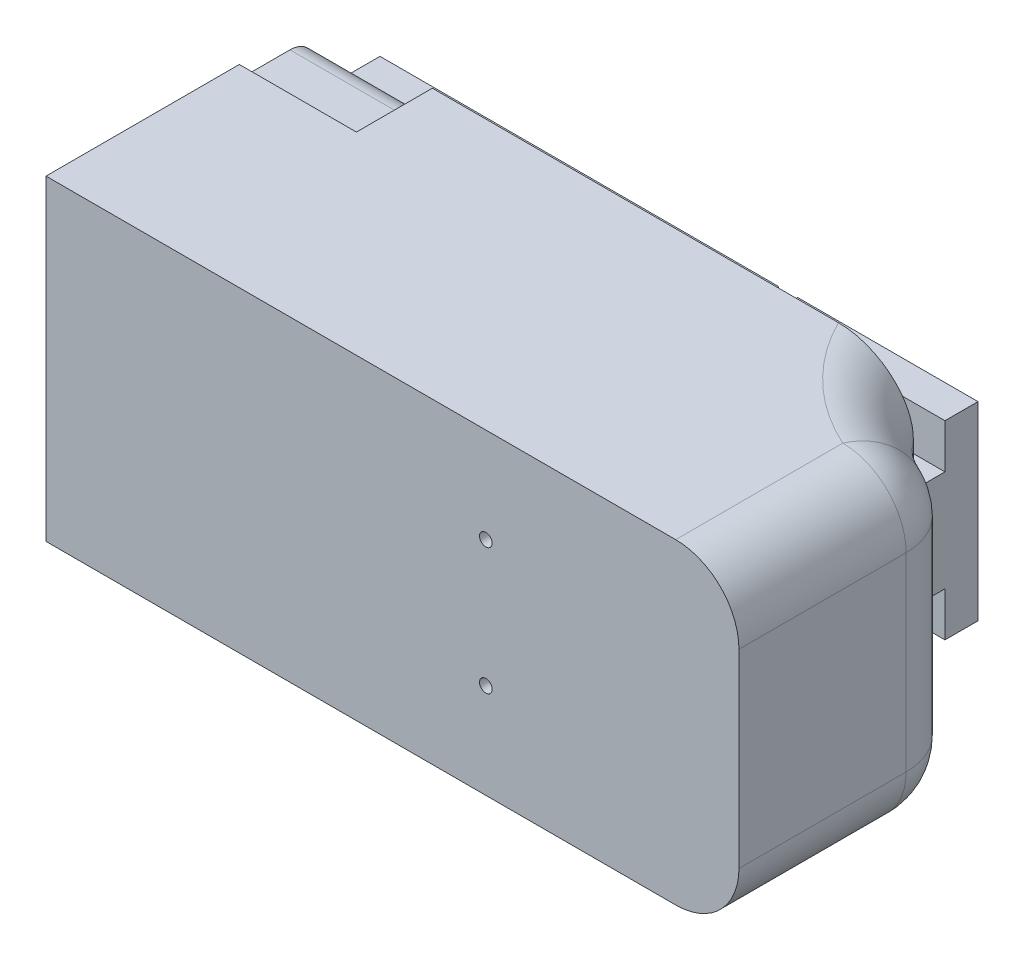
SolidWorks part; units mm, degrees
ref_plane "Front Plane" through (0, 0, 0) normal (0, 0, 1) x (1, 0, 0)
ref_plane "Top Plane" through (0, 0, 0) normal (0, 1, 0) x (1, 0, 0)
ref_plane "Right Plane" through (0, 0, 0) normal (1, 0, 0) x (0, 0, -1)
sketch "Sketch1" plane through (0, 0, 0) normal (0, 0, 1) x (1, 0, 0)
  line L0 (0, 0) -> (0, 50)
  line L1 (0, 50) -> (109.5, 50)
  line L2 (109.5, 50) -> (109.5, 0)
  line L3 (109.5, 0) -> (0, 0)
  dimension "D1" = 109.5
  dimension "D2" = 50
extrude "Boss-Extrude1" add sketch "Sketch1" along normal blind 52.55
sketch "Sketch2" plane through (0, 0, 0) normal (0, -1, 0) x (1, 0, 0)
  line L0 (0, 10) -> (109.5, 10)
  line L1 (0, 52.55) -> (0, 0) construction
  line L2 (109.5, 52.55) -> (109.5, 0) construction
  line L3 (0, 52.55) -> (109.5, 52.55) construction
  line L4 (0, 10) -> (0, 0)
  line L5 (0, 0) -> (109.5, 0)
  line L6 (109.5, 0) -> (109.5, 10)
  dimension "D1" = 42.55
extrude "Cut-Extrude1" cut sketch "Sketch2" against normal blind 10
sketch "Sketch3" plane through (0, 0, 0) normal (0, -1, 0) x (1, 0, 0)
  line L0 (0, 22) -> (18.5, 22)
  line L1 (0, 52.55) -> (0, 10) construction
  line L2 (18.5, 22) -> (18.5, 10)
  line L3 (109.5, 10) -> (0, 10) construction
  line L4 (0, 22) -> (0, 10)
  line L5 (0, 10) -> (18.5, 10)
  dimension "D1" = 18.5
  dimension "D2" = 12
extrude "Cut-Extrude2" cut sketch "Sketch3" against normal blind 2
fillet "Fillet1" radius 4 1 edges at (9.25, 2, 10)
sketch "Sketch4" plane through (0, 10, 0) normal (0, -1, 0) x (1, 0, 0)
  line L0 (18.5, 10) -> (18.5, 5)
  line L1 (109.5, 10) -> (0, 10) construction
  line L2 (18.5, 5) -> (109.5, 5)
  line L3 (109.5, 0) -> (109.5, 10) construction
  line L4 (109.5, 5) -> (109.5, 10)
  line L5 (109.5, 10) -> (18.5, 10)
  line L6 (0, 10) -> (0, 0) construction
  dimension "D1" = 18.5
  dimension "D2" = 5
extrude "Cut-Extrude3" cut sketch "Sketch4" against normal blind 7
sketch "Sketch5" plane through (0, 10, 0) normal (0, -1, 0) x (1, 0, 0)
  line L0 (94.5, 0) -> (94.5, 10)
  line L1 (0, 0) -> (109.5, 0) construction
  line L2 (109.5, 52.55) -> (109.5, 10) construction
  line L3 (94.5, 10) -> (117.8937, 10)
  line L4 (117.8937, 10) -> (117.8937, 0)
  line L5 (117.8937, 0) -> (94.5, 0)
  dimension "D1" = 10
  dimension "D2" = 15
extrude "Cut-Extrude4" cut sketch "Sketch5" against normal through all
sketch "Sketch6" plane through (0, 50, 0) normal (0, 1, 0) x (1, 0, 0)
  line L1 (94.5, -10) -> (0, -10)
  line L2 (0, -52.55) -> (0, 0) construction
  line L3 (0, -10) -> (0, 0)
  line L4 (0, 0) -> (94.5, 0)
  line L5 (94.5, 0) -> (94.5, -10)
extrude "Cut-Extrude5" cut sketch "Sketch6" against normal blind 10
sketch "Sketch8" plane through (0, 50, 0) normal (0, 1, 0) x (1, 0, 0)
  line L0 (0, -22) -> (18.5, -22)
  line L1 (0, -52.55) -> (0, -10) construction
  line L2 (18.5, -22) -> (18.5, -10)
  line L3 (109.5, -10) -> (0, -10) construction
  line L4 (18.5, -10) -> (0, -10)
  line L5 (0, -10) -> (0, -22)
  dimension "D1" = 18.5
  dimension "D2" = 12
extrude "Cut-Extrude6" cut sketch "Sketch8" against normal blind 2
fillet "Fillet2" radius 4 1 edges at (9.25, 48, 10)
sketch "Sketch9" plane through (0, 40, 0) normal (0, 1, 0) x (1, 0, 0)
  line L6 (18.5, -10) -> (18.5, -5)
  line L7 (0, -10) -> (94.5, -10) construction
  line L8 (18.5, -5) -> (94.5, -5)
  line L9 (94.5, -10) -> (94.5, 0) construction
  line L10 (94.5, -5) -> (94.5, -10)
  line L11 (94.5, -10) -> (18.5, -10)
  line L12 (0, 0) -> (0, -10) construction
  dimension "D1" = 18.5
  dimension "D2" = 5
extrude "Cut-Extrude7" cut sketch "Sketch9" against normal blind 7
sketch "Sketch10" plane through (0, 40, 0) normal (0, 1, 0) x (1, 0, 0)
  line L0 (94.5, 0) -> (0, 0) construction
  line L1 (109.5, -52.55) -> (109.5, -10) construction
  circle A0 centre (64.5, 0) radius 1.5
  dimension "D2" = 3
  dimension "D1" = 45
extrude "Cut-Extrude8" cut sketch "Sketch10" against normal through all
sketch "Sketch11" plane through (0, 0, 52.55) normal (0, 0, 1) x (1, 0, 0)
  line L0 (109.5, 0) -> (109.5, 50) construction
  line L1 (0, 0) -> (109.5, 0) construction
  circle A0 centre (69.5, 15) radius 1
  circle A1 centre (69.5, 35) radius 1
  dimension "D3" = 2
  dimension "D4" = 2
  dimension "D1" = 40
  dimension "D2" = 40
  dimension "D5" = 20
  dimension "D6" = 15
extrude "Cut-Extrude9" cut sketch "Sketch11" against normal blind 7.55
sketch "Sketch12" plane through (0, 50, 0) normal (0, 1, 0) x (1, 0, 0)
  line L0 (109.5, -10) -> (18.5, -10) construction
  line L1 (109.5, -52.55) -> (109.5, -10) construction
  line L2 (94.5, -10) -> (94.5, -5) construction
  line L3 (94.5, -10) -> (109.5, -10)
  line L4 (109.5, -10) -> (109.5, -18.85)
  line L5 (109.5, -52.55) -> (0, -52.55) construction
  arc A1 (109.5, -18.85) -> (94.5, -10) centre (113.9081, 5.7583) cw
  dimension "D1" = 25
  dimension "D2" = 0
  dimension "D3" = 33.7
extrude "Cut-Extrude10" cut sketch "Sketch12" against normal through all
fillet "Fillet3" radius 10 1 edges at (109.5, 25, 18.85)
sketch "Sketch13" plane through (0, 0, 0) normal (-1, 0, 0) x (0, 0, 1)
  line L0 (52.55, 50) -> (52.55, 0) construction
  line L1 (52.55, 50) -> (22, 50) construction
  line L2 (52.55, 0) -> (22, 0) construction
  circle A0 centre (37.552, 35) radius 2.5
  circle A1 centre (37.552, 15) radius 2.5
  dimension "D1" = 5
  dimension "D2" = 5
  dimension "D3" = 14.998
  dimension "D4" = 15
  dimension "D5" = 15
  dimension "D6" = 14.998
extrude "Cut-Extrude11" cut sketch "Sketch13" against normal blind 8
fillet "Fillet4" radius 10 3 edges at (98.6485, 50, 14.0443) (107.9014, 50, 20.7148) (109.5, 50, 39.3442)
fillet "Fillet5" radius 10 3 edges at (98.6485, 0, 14.0443) (107.9014, 0, 20.7148) (109.5, 0, 39.3442)
sketch "Sketch15" plane through (0, 0, 0) normal (0, 0, -1) x (-1, 0, 0)
  line L0 (0, 10) -> (0, 40)
  line L1 (0, 40) -> (-63, 40)
  line L2 (-63, 40) -> (-63, 10)
  line L3 (-63, 10) -> (0, 10)
  line L4 (-94.5, 10) -> (-66, 10)
  line L5 (-66, 10) -> (-66, 40)
  line L6 (-66, 40) -> (-94.5, 40)
  line L7 (-94.5, 40) -> (-94.5, 10)
extrude "Boss-Extrude2" add sketch "Sketch15" along normal blind 0.222
